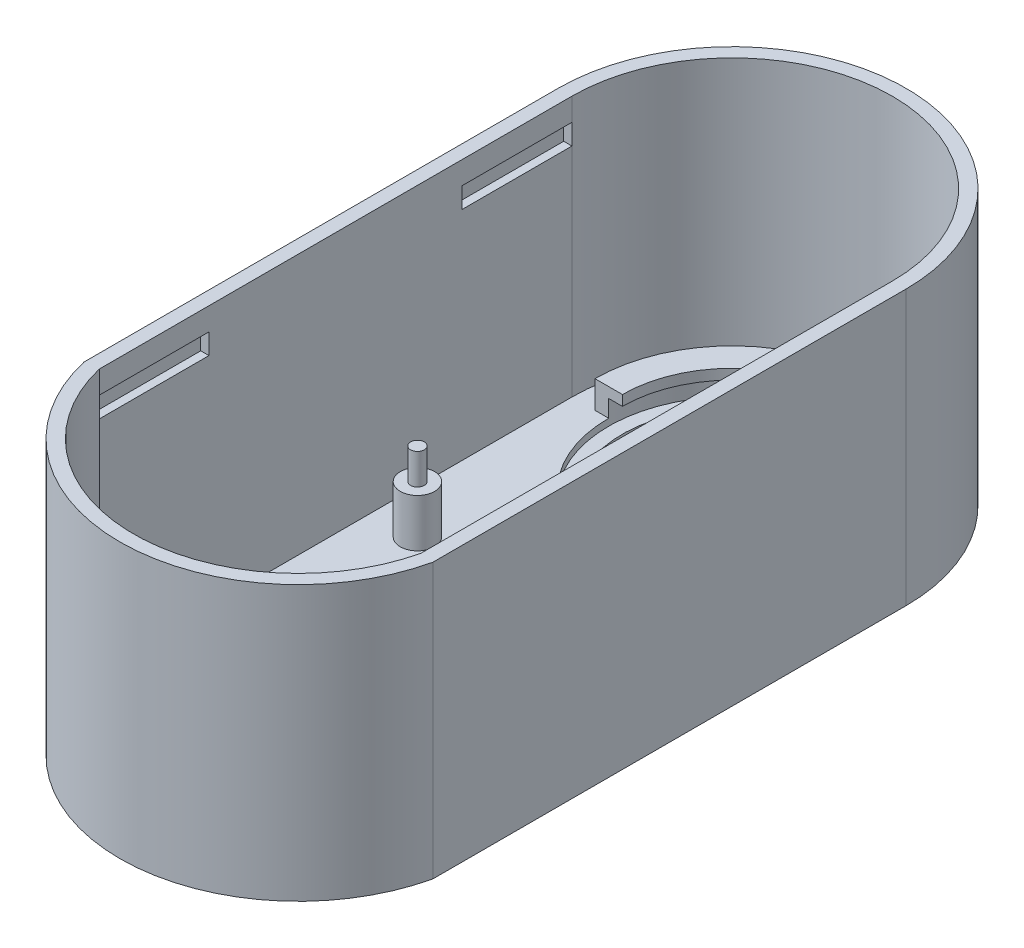
SolidWorks part; units mm, degrees
ref_plane "Alzado" through (0, 0, 0) normal (0, 0, 1) x (1, 0, 0)
ref_plane "Planta" through (0, 0, 0) normal (0, 1, 0) x (1, 0, 0)
ref_plane "Vista lateral" through (0, 0, 0) normal (1, 0, 0) x (0, 0, -1)
sketch "Croquis1" plane through (0, 0, 0) normal (0, 1, 0) x (1, 0, 0)
  line L13 (-64.418, -7.8768) -> (-37.918, -7.8768) construction
  line L14 (-64.418, -7.8768) -> (-64.418, -56.8768) construction
  line L15 (-64.418, -56.8768) -> (-37.918, -56.8768) construction
  line L16 (-37.918, -7.8768) -> (-37.918, -56.8768) construction
  line L18 (-70.668, 29.7663) -> (-31.668, 29.7663) construction
  line L19 (-31.668, 29.7663) -> (-31.668, -42.6244) construction
  line L20 (-31.668, -42.6244) -> (-70.668, -42.6244) construction
  line L21 (-70.668, -42.6244) -> (-70.668, 29.7663) construction
  line L22 (-76.5277, 21.978) -> (-25.8083, 21.978) construction
  line L23 (-28.3083, -46.7452) -> (-28.3083, 21.978)
  line L24 (-66.168, 27.1087) -> (-36.168, 27.1087) construction
  line L25 (-74.0277, -46.8931) -> (-74.0277, 21.978)
  line L27 (-66.168, 27.1087) -> (-66.168, -2.8913) construction
  line L28 (-66.168, -2.8913) -> (-36.168, -2.8913) construction
  line L29 (-76.5277, -47.1889) -> (-76.5277, 21.978)
  line L30 (-25.8083, -47.0331) -> (-25.8083, 21.978)
  line L31 (-36.168, 27.1087) -> (-36.168, -2.8913) construction
  arc A11 (-76.5277, -47.1889) -> (-25.8083, -47.0331) centre (-51.186, -41.2624) ccw
  arc A12 (-74.0277, 21.978) -> (-28.3083, 21.978) centre (-51.168, 21.978) cw
  circle A13 centre (-51.168, 21.978) radius 18 construction
  circle A14 centre (-51.168, -12.9154) radius 6
  arc A15 (-74.0277, -46.8931) -> (-28.3083, -46.7452) centre (-51.186, -41.2624) ccw
  arc A16 (-76.5277, 21.978) -> (-25.8083, 21.978) centre (-51.168, 21.978) cw
  circle A21 centre (-51.168, 21.978) radius 16
extrude "Saliente-Extruir5" add sketch "Croquis1" along normal blind 40 contours A16 L30 A11 L29
sketch "Croquis16" plane through (0, 40, 0) normal (0, 1, 0) x (1, 0, 0)
  line L4 (-74.5277, 21.978) -> (-74.5277, -46.9535)
  line L5 (-27.8083, -46.804) -> (-27.8083, 21.978)
  line L6 (-74.5277, 21.978) -> (-74.5277, -46.9535)
  line L7 (-27.8083, -46.804) -> (-27.8083, 21.978)
  arc A4 (-74.5277, -46.9535) -> (-27.8083, -46.804) centre (-51.186, -41.2624) ccw
  arc A5 (-27.8083, 21.978) -> (-74.5277, 21.978) centre (-51.168, 21.978) ccw
  arc A6 (-74.5277, -46.9535) -> (-27.8083, -46.804) centre (-51.186, -41.2624) ccw
  arc A7 (-27.8083, 21.978) -> (-74.5277, 21.978) centre (-51.168, 21.978) ccw
  dimension "D1" = 2
extrude "Cortar-Extruir3" cut sketch "Croquis16" against normal blind 38
sketch "Croquis19" plane through (0, 2, 0) normal (0, 1, 0) x (1, 0, 0)
  circle A0 centre (-51.168, 21.978) radius 16
extrude "Cortar-Extruir4" cut sketch "Croquis19" against normal blind 16 contours A0
sketch "Croquis22" plane through (0, 2, 0) normal (0, 1, 0) x (1, 0, 0)
  circle A0 centre (-51.168, -14.8107) radius 6
extrude "Cortar-Extruir6" cut sketch "Croquis22" against normal blind 16 contours A0
sketch "Croquis23" plane through (-74.5277, 0, 0) normal (1, 0, 0) x (0, 0, -1)
  line L0 (21.978, 40) -> (-46.9535, 40) construction
  line L1 (-46.9535, 2) -> (-46.9535, 40) construction
  line L2 (21.978, 2) -> (21.978, 40) construction
  line L3 (-46.9535, 36.7) -> (-30.9535, 36.7)
  line L4 (-46.9535, 36.7) -> (-46.9535, 33.7)
  line L5 (-46.9535, 33.7) -> (-30.9535, 33.7)
  line L6 (-30.9535, 36.7) -> (-30.9535, 33.7)
  line L7 (21.978, 36.7) -> (5.978, 36.7)
  line L8 (21.978, 36.7) -> (21.978, 33.7)
  line L9 (21.978, 33.7) -> (5.978, 33.7)
  line L10 (5.978, 36.7) -> (5.978, 33.7)
  dimension "D1" = 3
  dimension "D2" = 3.3
  dimension "D3" = 3
  dimension "D4" = 3.3
sketch "Croquis24" plane through (-27.8083, 0, 0) normal (-1, 0, 0) x (0, 0, 1)
  line L0 (-21.978, 2) -> (-21.978, 40) construction
  line L2 (-21.978, 36.7) -> (-5.978, 36.7)
  line L3 (-21.978, 36.7) -> (-21.978, 33.7)
  line L4 (-21.978, 33.7) -> (-5.978, 33.7)
  line L5 (-5.978, 36.7) -> (-5.978, 33.7)
  line L6 (46.804, 40) -> (-21.978, 40) construction
  line L8 (46.804, 36.7) -> (30.804, 36.7)
  line L9 (46.804, 36.7) -> (46.804, 33.7)
  line L10 (46.804, 33.7) -> (30.804, 33.7)
  line L11 (30.804, 36.7) -> (30.804, 33.7)
  dimension "D1" = 3.3
  dimension "D2" = 3
  dimension "D3" = 16
  dimension "D4" = 16
  dimension "D5" = 3.3
sketch "Croquis25" plane through (0, 2, 0) normal (0, 1, 0) x (1, 0, 0)
  line L8 (-54.168, -6.8107) -> (-48.168, -6.8107)
  line L9 (-54.168, -6.8107) -> (-54.168, -22.8107)
  line L10 (-54.168, -22.8107) -> (-48.168, -22.8107)
  line L11 (-48.168, -6.8107) -> (-48.168, -22.8107)
extrude "Cortar-Extruir10" cut sketch "Croquis25" against normal blind 0.6
sketch "Croquis28" plane through (0, 2, 0) normal (0, 1, 0) x (1, 0, 0)
  circle A0 centre (-51.168, 21.978) radius 18
extrude "Cortar-Extruir11" cut sketch "Croquis28" against normal blind 1
sketch "Croquis29" plane through (0, 2, 0) normal (0, 1, 0) x (1, 0, 0)
  line L0 (-71.168, 21.978) -> (-31.168, 21.978)
  arc A0 (-31.168, 21.978) -> (-71.168, 21.978) centre (-51.168, 21.978) ccw
extrude "Saliente-Extruir7" add sketch "Croquis29" along normal blind 4 contours L0 A0
sketch "Croquis30" plane through (0, 6, 0) normal (0, 1, 0) x (1, 0, 0)
  circle A0 centre (-51.168, 21.978) radius 16
extrude "Cortar-Extruir12" cut sketch "Croquis30" against normal blind 34
sketch "Croquis31" plane through (0, 1, 0) normal (0, 1, 0) x (1, 0, 0)
  circle A0 centre (-51.168, 21.978) radius 18
extrude "Cortar-Extruir13" cut sketch "Croquis31" along normal blind 3.5
sketch "Croquis32" plane through (0, 2, 0) normal (0, 1, 0) x (1, 0, 0)
  line L0 (-34.2083, -46.804) -> (-34.2083, -49.804)
  line L1 (-74.5277, -29.8997) -> (-70.5277, -29.8997)
  line L2 (-74.5277, 21.978) -> (-74.5277, -46.9535) construction
  line L3 (-70.5277, -29.8997) -> (-70.5277, -55.5145)
  line L4 (-70.5277, -29.8997) -> (-70.5277, 19.1385)
  line L5 (-27.8083, -39.0604) -> (-31.8083, -39.0604)
  line L6 (-27.8083, -46.804) -> (-27.8083, 21.978) construction
  line L7 (-31.8083, -39.0604) -> (-31.8083, 19.1385)
  line L8 (-31.8083, -39.0604) -> (-31.8083, -53.99)
  line L9 (-31.8083, -53.99) -> (-70.5277, -53.99)
  line L10 (-27.8083, -46.804) -> (-34.2083, -46.804)
  line L11 (-74.5277, -46.9535) -> (-68.1277, -46.9535)
  line L12 (-68.1277, -46.9535) -> (-68.1277, -49.9535)
  line L13 (-68.1277, -49.9535) -> (-68.1277, -6.9535)
  line L14 (-34.2083, -49.804) -> (-34.2083, -6.804)
  arc A0 (-74.5277, -46.9535) -> (-27.8083, -46.804) centre (-51.186, -41.2624) ccw construction
  circle A1 centre (-68.1277, -49.9535) radius 2.5
  circle A2 centre (-34.2083, -49.804) radius 2.5
  circle A3 centre (-68.1277, -6.9535) radius 2.5
  circle A4 centre (-34.2083, -6.804) radius 2.5
  dimension "D4" = 3
  dimension "D6" = 3
  dimension "D7" = 43
  dimension "D1" = 4
  dimension "D2" = 4
  dimension "D3" = 6.4
  dimension "D5" = 6.4
  dimension "D8" = 43
other "Alinear grupo1"
extrude "Cortar-Extruir14" cut sketch "Croquis24" against normal blind 1.2 contours L11 L10 L9 L8 | L3 L4 L5 L2
extrude "Cortar-Extruir15" cut sketch "Croquis23" against normal blind 1.2 contours L10 L9 L8 L7 | L5 L6 L3 L4
extrude "Saliente-Extruir8" add sketch "Croquis32" along normal blind 7 contours A1 | A2 | A3 | A4
sketch "Croquis47" plane through (0, 9, 0) normal (0, 1, 0) x (1, 0, 0)
  circle A0 centre (-34.2083, -6.804) radius 1
sketch "Croquis48" plane through (0, 9, 0) normal (0, 1, 0) x (1, 0, 0)
  circle A0 centre (-68.1277, -6.9535) radius 1
sketch "Croquis49" plane through (0, 9, 0) normal (0, 1, 0) x (1, 0, 0)
  circle A0 centre (-34.2083, -49.804) radius 1
sketch "Croquis50" plane through (0, 9, 0) normal (0, 1, 0) x (1, 0, 0)
  circle A0 centre (-68.1277, -49.9535) radius 1
extrude "Saliente-Extruir9" add sketch "Croquis49" along normal blind 4.5 contours A0
extrude "Saliente-Extruir10" add sketch "Croquis47" along normal blind 4.5 contours A0
extrude "Saliente-Extruir11" add sketch "Croquis48" along normal blind 4.5 contours A0
extrude "Saliente-Extruir12" add sketch "Croquis50" along normal blind 4.5 contours A0
